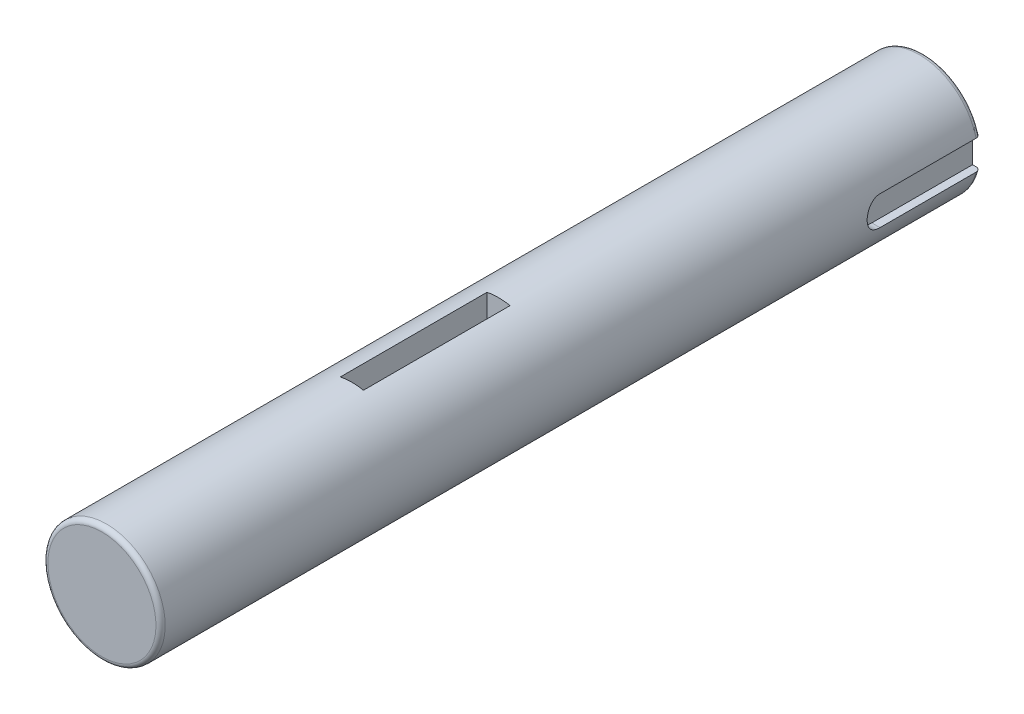
SolidWorks part; units mm, degrees
material "AISI 1045 Steel, cold drawn"
ref_plane "Front Plane" through (0, 0, 0) normal (0, 0, 1) x (1, 0, 0)
ref_plane "Top Plane" through (0, 0, 0) normal (0, 1, 0) x (1, 0, 0)
ref_plane "Right Plane" through (0, 0, 0) normal (1, 0, 0) x (0, 0, -1)
sketch "Sketch1" plane through (0, 0, 0) normal (1, 0, 0) x (0, 0, -1)
  line L0 (0, 0) -> (-356, 0) construction
  line L1 (0, 0) -> (0, 23.4)
  line L2 (-2, 25.4) -> (-354, 25.4)
  line L3 (-356, 23.4) -> (-356, 0)
  line L4 (0, 0) -> (-356, 0)
  arc A1 (-354, 25.4) -> (-356, 23.4) centre (-354, 23.4) ccw
  arc A2 (0, 23.4) -> (-2, 25.4) centre (-2, 23.4) ccw
  point P8 (-356, 25.4)
  point P11 (0, 25.4)
  dimension "D1" = 356
  dimension "D3" = 2
  dimension "D2" = 25.4
revolve "Revolve1" add sketch "Sketch1" angle 360 about L0
ref_plane "Plane1" through (0, 0, 0) normal (0, 0, -1) x (-1, 0, 0)
ref_plane "Plane2" through (25.4, 0, 0) normal (1, 0, 0) x (0, 0, -1)
sketch "Sketch5" plane through (0, 0, 0) normal (0, 0, -1) x (-1, 0, 0)
  line L1 (-21.05, 6.35) -> (-25.4, 6.35)
  line L2 (-21.05, 6.35) -> (-21.05, -6.35)
  line L3 (-21.05, -6.35) -> (-25.4, -6.35)
  line L4 (-25.4, 6.35) -> (-25.4, -6.35)
  line L5 (-21.05, 0) -> (23.4, 0) construction
  line L6 (-25.4, 27.94) -> (-25.4, -27.94) construction
  circle A0 centre (0, 0) radius 23.4 construction
  dimension "D2" = 44.45
  dimension "D3" = 12.7
sketch "Sketch6" plane through (25.4, 0, 0) normal (1, 0, 0) x (0, 0, -1)
  line L0 (0, 6.35) -> (0, -6.35) construction
  line L1 (0, 6.35) -> (-43.65, 6.35)
  line L2 (0, 6.35) -> (0, -6.35)
  line L3 (0, -6.35) -> (-43.65, -6.35)
  line L5 (0, -25.74) -> (0, 25.74) construction
  arc A0 (-43.65, -6.35) -> (-43.65, 6.35) centre (-43.65, 0) cw
  point P1 (-50, 0)
  dimension "D2" = 6.35
  dimension "D1" = 50
  dimension "D3" = 12.7
  dimension "D4" = 43.65
  dimension "D5" = 16.554
extrude "Cut-Extrude7" cut sketch "Sketch6" against normal up to vertex (4.35 mm away) up to point (21.05, 6.35, 0)
ref_plane "Plane4" through (0, 0, 247.75) normal (0, 0, 1) x (1, 0, 0)
ref_plane "Plane3" through (0, 0, 356) normal (0, 0, 1) x (1, 0, 0)
sketch "Sketch7" plane through (0, 0, 247.75) normal (0, 0, 1) x (1, 0, 0)
  line L0 (0, 25.4) -> (0, 0) construction
  line L2 (-5, 24.903) -> (-5, 14.903)
  line L3 (-5, 14.903) -> (5, 14.903)
  line L4 (5, 24.903) -> (5, 14.903)
  line L9 (0, 0) -> (23.4, 0) construction
  circle A0 centre (0, 0) radius 25.4 construction
  arc A1 (-5, 24.903) -> (5, 24.903) centre (0, 0) cw
  circle A3 centre (0, 0) radius 23.4 construction
  point P15 (0, 14.903)
  dimension "D1" = 10
  dimension "D2" = 10
extrude "Cut-Extrude8" cut sketch "Sketch7" against normal blind 63.5
